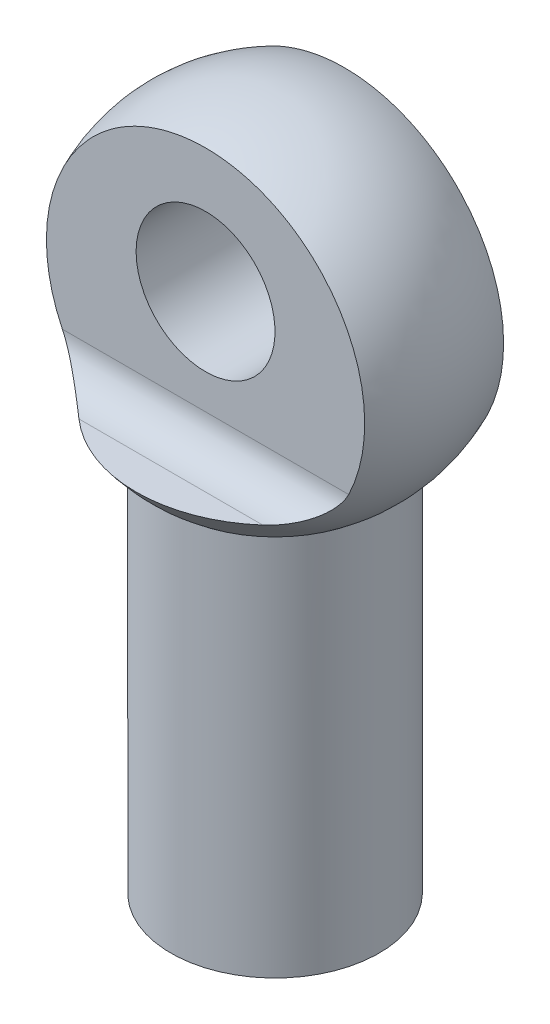
SolidWorks part; units mm, degrees
ref_plane "Alzado" through (0, 0, 0) normal (0, 0, 1) x (1, 0, 0)
ref_plane "Planta" through (0, 0, 0) normal (0, 1, 0) x (1, 0, 0)
ref_plane "Vista lateral" through (0, 0, 0) normal (1, 0, 0) x (0, 0, -1)
sketch "Croquis4" plane through (0, 0, 0) normal (1, 0, 0) x (0, 0, -1)
  line L1 (0, 0) -> (-3, 0)
  line L2 (0, 0) -> (0, 11)
  line L3 (0, 11) -> (-3, 11)
  line L4 (-3, 0) -> (-3, 11)
  dimension "D1" = 3
  dimension "D2" = 11
revolve "Revolución2" add sketch "Croquis4" angle 360 about L2
cosmetic thread "Rosca cosmética2" parameters "D1"=8, "D2"=4.891
sketch "Croquis5" plane through (0, 0, 0) normal (1, 0, 0) x (0, 0, -1)
  line L0 (0, -1000) -> (0, 10) construction
  line L1 (0, 20) -> (0, 11)
  line L2 (3, 11) -> (-3, 11) construction
  line L4 (-3, 0) -> (3, 0) construction
  line L5 (0, 20) -> (0, 50000) construction
  line L7 (0, 11) -> (-3, 11)
  arc A0 (0, 20) -> (-3, 11) centre (0, 15) ccw
  point P7 (0, 11)
  dimension "D1" = 20
  dimension "D2" = 10
  dimension "D3" = 9
revolve "Revolución3" add sketch "Croquis5" angle 360 about L5
sketch "Croquis7" plane through (0, 0, 0) normal (1, 0, 0) x (0, 0, -1)
  line L0 (0, 20) -> (0, 50020) construction
  line L18 (2, 12) -> (2, 20)
  line L19 (2, 12) -> (6, 12)
  line L21 (2, 20) -> (6, 20)
  line L22 (6, 12) -> (6, 20)
  line L27 (3, 11) -> (-3, 11) construction
  arc A2 (3, 11) -> (-3, 11) centre (0, 15) ccw construction
  point P8 (0, 20)
  dimension "D1" = 2
  dimension "D2" = 1
  dimension "D4" = 8
  dimension "D5" = 4
extrude "Cortar-Extruir1" cut sketch "Croquis7" against normal mid plane 15
sketch "Croquis9" plane through (0, 0, 0) normal (1, 0, 0) x (0, 0, -1)
  line L0 (0, 11) -> (0, 50011) construction
  line L1 (3, 11) -> (-3, 11) construction
  line L2 (-3.1093, 11) -> (-50003.1093, 11) construction
  line L3 (0.1418, 20) -> (-49999.8582, 20) construction
  line L4 (-3, 0) -> (3, 0) construction
  line L5 (-2, 12) -> (-7, 12)
  line L6 (-2, 12) -> (-2, 20)
  line L7 (-2, 20) -> (-7, 20)
  line L8 (-7, 12) -> (-7, 20)
  point P4 (0, 11)
  dimension "D1" = 1
  dimension "D2" = 11
  dimension "D3" = 8
  dimension "D4" = 2
  dimension "D5" = 5
extrude "Cortar-Extruir2" cut sketch "Croquis9" against normal mid plane 15
ref_plane "Plano2" through (0, 0, 0) normal (0, 0, -1) x (-1, 0, 0)
fillet "Redondeo3" radius 1 2 edges at (0, 12, 2) (0, 12, -2)
sketch "Croquis10" plane through (0, 0, 0) normal (0, 0, -1) x (-1, 0, 0)
  line L1 (-4.1231, 13) -> (4.1231, 13) construction
  circle A0 centre (0, 16) radius 2
  arc A1 (4.1231, 13) -> (-4.1231, 13) centre (0, 15) ccw construction
  point P7 (0, 19.5826)
  dimension "D2" = 4
  dimension "D1" = 3
  dimension "D3" = 3.5826
extrude "Cortar-Extruir3" cut sketch "Croquis10" against normal mid plane 15
